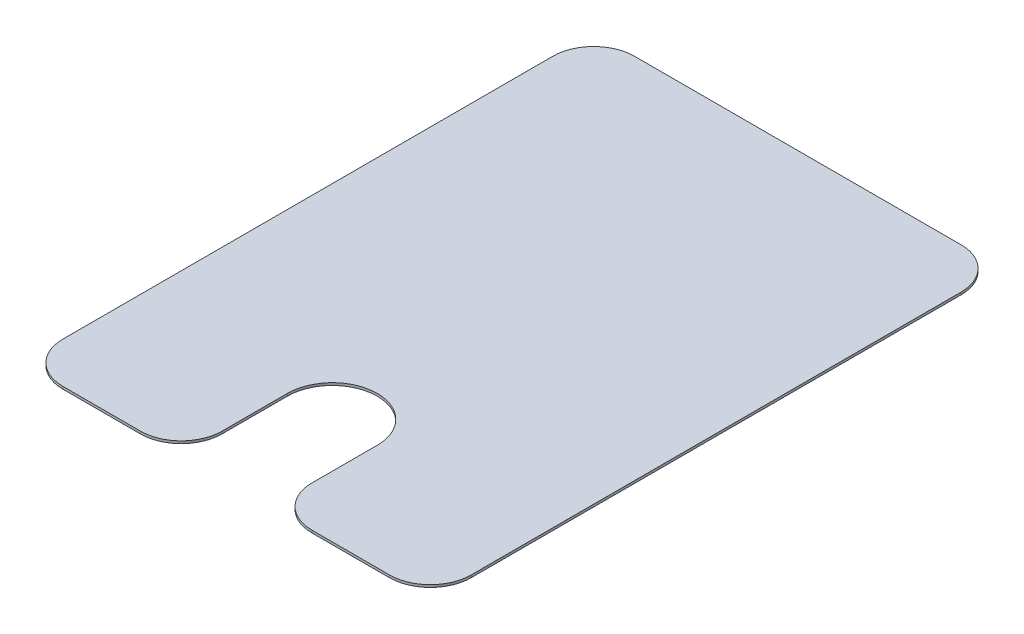
SolidWorks part; units mm, degrees
ref_plane "前视基准面" through (0, 0, 0) normal (0, 0, 1) x (1, 0, 0)
ref_plane "上视基准面" through (0, 0, 0) normal (0, 1, 0) x (1, 0, 0)
ref_plane "右视基准面" through (0, 0, 0) normal (1, 0, 0) x (0, 0, -1)
other "Configuration Table"
sketch "草图1" plane through (0, 0, 0) normal (0, 1, 0) x (1, 0, 0)
  line L0 (-55, -220) -> (-55, -300)
  line L1 (-200, -350) -> (-105, -350)
  line L2 (-250, -300) -> (-250, 300)
  line L3 (-200, 350) -> (200, 350)
  line L4 (250, -300) -> (250, 300)
  line L5 (-250, -350) -> (250, 350) construction
  line L6 (-250, 350) -> (250, -350) construction
  line L7 (55, -220) -> (55, -300)
  line L8 (105, -350) -> (200, -350)
  arc A0 (200, -350) -> (250, -300) centre (200, -300) ccw
  arc A1 (-250, 300) -> (-200, 350) centre (-200, 300) cw
  arc A2 (-200, -350) -> (-250, -300) centre (-200, -300) cw
  arc A3 (200, 350) -> (250, 300) centre (200, 300) cw
  arc A4 (55, -220) -> (-55, -220) centre (0, -220) ccw
  arc A5 (-55, -300) -> (-105, -350) centre (-105, -300) cw
  arc A6 (105, -350) -> (55, -300) centre (105, -300) cw
  point P0 (0, 0)
  dimension "D3" = 50
  dimension "D4" = 110
  dimension "D5" = 50
  dimension "D1" = 700
  dimension "D2" = 500
extrude "凸台-拉伸1" add sketch "草图1" along normal blind 3
